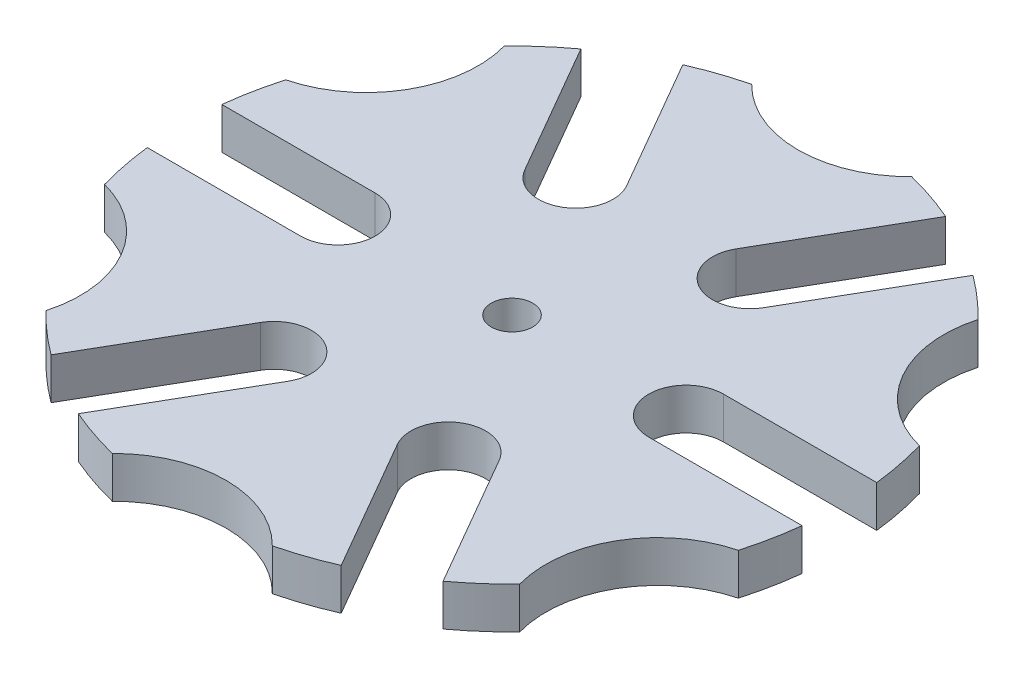
SolidWorks part; units mm, degrees
ref_plane "前视基准面" through (0, 0, 0) normal (0, 0, 1) x (1, 0, 0)
ref_plane "上视基准面" through (0, 0, 0) normal (0, 1, 0) x (1, 0, 0)
ref_plane "右视基准面" through (0, 0, 0) normal (1, 0, 0) x (0, 0, -1)
other "Configuration Table"
sketch "草图4" plane through (0, 0, 0) normal (0, 1, 0) x (1, 0, 0)
  line L0 (0, 0) -> (34.7481, 0)
  line L1 (0, 0) -> (37.1789, 21.4652)
  line L2 (14, 3) -> (26.3296, 3)
  line L3 (14, -3) -> (26.3296, -3)
  line L4 (9.5981, -10.6244) -> (15.7629, -21.3021)
  line L5 (4.4019, -13.6244) -> (10.5667, -24.3021)
  line L6 (-4.4019, -13.6244) -> (-10.5667, -24.3021)
  line L7 (-9.5981, -10.6244) -> (-15.7629, -21.3021)
  line L8 (-14, -3) -> (-26.3296, -3)
  line L9 (-14, 3) -> (-26.3296, 3)
  line L10 (-9.5981, 10.6244) -> (-15.7629, 21.3021)
  line L11 (-4.4019, 13.6244) -> (-10.5667, 24.3021)
  line L12 (4.4019, 13.6244) -> (10.5667, 24.3021)
  line L13 (9.5981, 10.6244) -> (15.7629, 21.3021)
  circle A0 centre (0, 0) radius 14
  circle A1 centre (0, 0) radius 32
  circle A2 centre (0, 0) radius 26.5
  circle A3 centre (27.714, 16.0007) radius 9
  circle A4 centre (14, 0) radius 3
  circle A5 centre (0, 0) radius 26.5
  circle A6 centre (27.714, -16.0007) radius 9
  circle A7 centre (7, -12.1244) radius 3
  circle A8 centre (0, 0) radius 26.5
  circle A9 centre (0, -32.0013) radius 9
  circle A10 centre (-7, -12.1244) radius 3
  circle A11 centre (0, 0) radius 26.5
  circle A12 centre (-27.714, -16.0007) radius 9
  circle A13 centre (-14, 0) radius 3
  circle A14 centre (0, 0) radius 26.5
  circle A15 centre (-27.714, 16.0007) radius 9
  circle A16 centre (-7, 12.1244) radius 3
  circle A17 centre (0, 0) radius 26.5
  circle A18 centre (0, 32.0013) radius 9
  circle A19 centre (7, 12.1244) radius 3
  point P15 (0, 0)
  point P63 (0, 0)
  dimension "D1" = 28
  dimension "D2" = 64
  dimension "D3" = 53
  dimension "D4" = 30
  dimension "D5" = 18
  dimension "D6" = 6
  dimension "D7" = 6
extrude "凸台-拉伸2" add sketch "草图4" along normal blind 10 contours A16 L10 A2 A15 L9 A13 A0 | A19 A0 A16 A13 A10 A7 A4 L0 L1 | A19 L12 A2 A18 L11 A16 A0 | A19 A0 L1 A3 A2 L13 | A4 L2 A2 A3 L1 A0 | A7 L4 A2 A6 L3 A4 A0 | A10 L6 A2 A9 L5 A7 A0 | A13 L8 A2 A12 L7 A10 A0 | A4 A0 L1 L0
scale "缩放比例2" scale about centroid uniform scaling yes scale factor 3
sketch "草图5" plane through (0, 0, 0) normal (1, 0, 0) x (0, 0, -1)
  line L0 (77.1219, 20) -> (77.1219, -10) construction
  line L1 (-77.1219, 20) -> (77.1219, 20)
  line L2 (-77.1219, 20) -> (-77.1219, 0)
  line L3 (-77.1219, 0) -> (77.1219, 0)
  line L4 (77.1219, 20) -> (77.1219, 0)
  dimension "D1" = 20
extrude "切除-拉伸1" cut sketch "草图5" against normal mid plane 227
sketch "草图6" plane through (0, -10, 0) normal (0, -1, 0) x (1, 0, 0)
  circle A0 centre (0, 0) radius 5
  dimension "D1" = 10
extrude "切除-拉伸2" cut sketch "草图6" against normal mid plane 227
